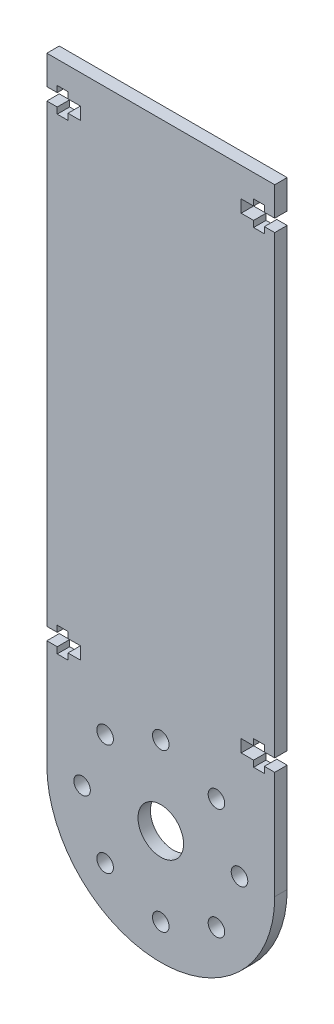
SolidWorks part; units mm, degrees
ref_plane "前视基准面" through (0, 0, 0) normal (0, 0, 1) x (1, 0, 0)
ref_plane "上视基准面" through (0, 0, 0) normal (0, 1, 0) x (1, 0, 0)
ref_plane "右视基准面" through (0, 0, 0) normal (1, 0, 0) x (0, 0, -1)
sketch "草图1" plane through (0, 0, 0) normal (0, 0, 1) x (1, 0, 0)
  line L261 (222.4534, -82.2166) -> (222.4534, -75.2166)
  line L277 (222.4534, -75.2166) -> (277.4534, -75.2166)
  line L278 (249.9534, -196.5371) -> (249.9534, -184.6737) construction
  line L279 (277.4534, -82.2166) -> (274.9534, -82.2166)
  line L280 (274.9534, -85.2166) -> (277.4534, -85.2166)
  line L281 (274.9534, -80.7166) -> (272.3534, -80.7166)
  line L282 (224.9534, -85.2166) -> (224.9534, -86.7166)
  line L283 (224.9534, -82.2166) -> (224.9534, -80.7166)
  line L284 (222.4534, -82.2166) -> (224.9534, -82.2166)
  line L285 (224.9534, -86.7166) -> (227.5534, -86.7166)
  line L286 (227.5534, -86.7166) -> (227.5534, -85.2166)
  line L287 (227.5534, -85.2166) -> (230.5534, -85.2166)
  line L288 (230.5534, -82.2166) -> (230.5534, -85.2166)
  line L289 (227.5534, -82.2166) -> (230.5534, -82.2166)
  line L290 (227.5534, -80.7166) -> (227.5534, -82.2166)
  line L291 (224.9534, -80.7166) -> (227.5534, -80.7166)
  line L292 (224.9534, -85.2166) -> (222.4534, -85.2166)
  line L293 (230.5534, -83.7166) -> (222.4534, -83.7166) construction
  line L294 (272.3534, -80.7166) -> (272.3534, -82.2166)
  line L295 (233.4534, -83.7166) -> (222.4534, -83.7166) construction
  line L296 (249.9534, -196.5371) -> (222.4534, -196.5371) construction
  line L297 (272.3534, -82.2166) -> (269.3534, -82.2166)
  line L298 (224.9534, -198.0371) -> (224.9534, -199.5371)
  line L299 (224.9534, -195.0371) -> (224.9534, -193.5371)
  line L300 (222.4534, -195.0371) -> (224.9534, -195.0371)
  line L301 (224.9534, -199.5371) -> (227.5534, -199.5371)
  line L302 (227.5534, -199.5371) -> (227.5534, -198.0371)
  line L303 (227.5534, -198.0371) -> (230.5534, -198.0371)
  line L304 (230.5534, -195.0371) -> (230.5534, -198.0371)
  line L305 (227.5534, -195.0371) -> (230.5534, -195.0371)
  line L306 (227.5534, -193.5371) -> (227.5534, -195.0371)
  line L307 (224.9534, -193.5371) -> (227.5534, -193.5371)
  line L308 (224.9534, -198.0371) -> (222.4534, -198.0371)
  line L309 (230.5534, -196.5371) -> (222.4534, -196.5371) construction
  line L321 (269.3534, -82.2166) -> (269.3534, -85.2166)
  line L322 (222.4534, -85.2166) -> (222.4534, -195.0371)
  line L323 (222.4534, -198.0371) -> (222.4534, -224.0371)
  line L326 (277.4534, -195.0371) -> (274.9534, -195.0371)
  line L327 (274.9534, -195.0371) -> (274.9534, -193.5371)
  line L328 (274.9534, -193.5371) -> (272.3534, -193.5371)
  line L329 (272.3534, -193.5371) -> (272.3534, -195.0371)
  line L330 (272.3534, -195.0371) -> (269.3534, -195.0371)
  line L331 (269.3534, -195.0371) -> (269.3534, -198.0371)
  line L332 (272.3534, -198.0371) -> (269.3534, -198.0371)
  line L333 (274.9534, -199.5371) -> (272.3534, -199.5371)
  line L334 (272.3534, -199.5371) -> (272.3534, -198.0371)
  line L335 (274.9534, -198.0371) -> (274.9534, -199.5371)
  line L336 (274.9534, -198.0371) -> (277.4534, -198.0371)
  line L348 (272.3534, -85.2166) -> (269.3534, -85.2166)
  line L360 (272.3534, -86.7166) -> (272.3534, -85.2166)
  line L361 (274.9534, -86.7166) -> (272.3534, -86.7166)
  line L365 (277.4534, -198.0371) -> (277.4534, -224.0371)
  line L366 (274.9534, -82.2166) -> (274.9534, -80.7166)
  line L367 (274.9534, -85.2166) -> (274.9534, -86.7166)
  line L368 (277.4534, -75.2166) -> (277.4534, -82.2166)
  line L369 (277.4534, -85.2166) -> (277.4534, -195.0371)
  line L370 (233.4534, -95.7897) -> (269.3534, -184.6737) construction
  line L371 (269.3534, -184.6737) -> (233.4534, -184.6737) construction
  line L372 (233.4534, -184.6737) -> (233.4534, -95.7897) construction
  line L373 (269.3534, -184.6737) -> (269.3534, -95.7897) construction
  line L374 (269.3534, -95.7897) -> (233.4534, -95.7897) construction
  circle A25 centre (249.9534, -224.0371) radius 27.5 construction
  arc A27 (277.4534, -224.0371) -> (222.4534, -224.0371) centre (249.9534, -224.0371) cw
  circle A28 centre (249.9534, -224.0371) radius 5.5
  circle A35 centre (249.9534, -224.0371) radius 19 construction
  circle A36 centre (249.9534, -205.0371) radius 2
  circle A37 centre (263.3884, -210.602) radius 2
  circle A38 centre (268.9534, -224.0371) radius 2
  circle A39 centre (263.3884, -237.4721) radius 2
  circle A40 centre (249.9534, -243.0371) radius 2
  circle A41 centre (236.5183, -237.4721) radius 2
  circle A42 centre (230.9534, -224.0371) radius 2
  circle A43 centre (236.5183, -210.602) radius 2
  dimension "D1" = 8
  dimension "D2" = 109.8205
extrude "凸台-拉伸1" add sketch "草图1" along normal blind 3
sketch "草图3" plane through (222.4534, 0, 0) normal (-1, 0, 0) x (0, 0, 1)
  line L0 (1.5, -198.0371) -> (1.5, -195.0371)
  line L1 (3, -198.0371) -> (0, -198.0371) construction
  line L2 (3, -195.0371) -> (0, -195.0371) construction
  circle A0 centre (1.5, -196.5371) radius 1.5
